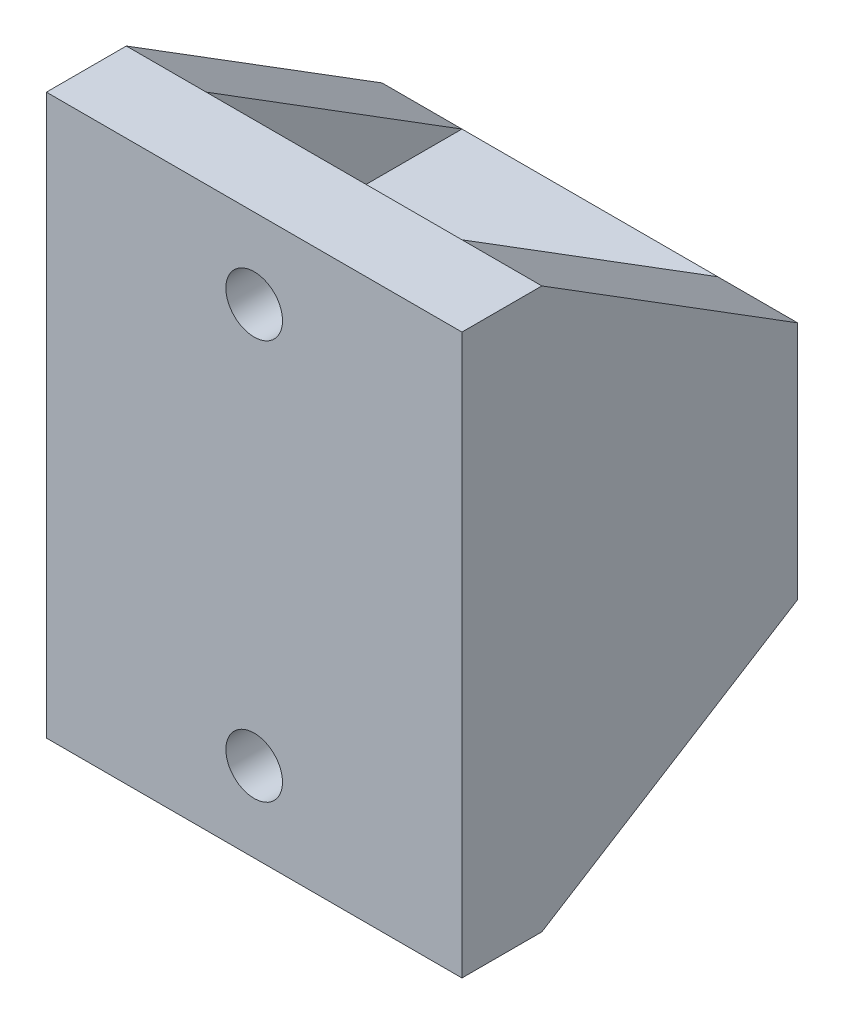
SolidWorks part; units mm, degrees
ref_plane "Face" through (0, 0, 0) normal (0, 0, 1) x (1, 0, 0)
ref_plane "Dessus" through (0, 0, 0) normal (0, 1, 0) x (1, 0, 0)
ref_plane "Droite" through (0, 0, 0) normal (1, 0, 0) x (0, 0, -1)
sketch "Esquisse1" plane through (0, 0, 0) normal (0, 0, 1) x (1, 0, 0)
  line L0 (-13.716, 4.3815) -> (-13.716, -4.3815)
  line L1 (-16.51, 9.525) -> (16.51, 9.525)
  line L2 (-16.51, 9.525) -> (-16.51, -9.525)
  line L3 (-16.51, -9.525) -> (16.51, -9.525)
  line L4 (16.51, 9.525) -> (16.51, -9.525)
  line L5 (-16.51, 9.525) -> (16.51, -9.525) construction
  line L6 (-16.51, -9.525) -> (16.51, 9.525) construction
  line L7 (-13.716, -4.3815) -> (13.716, -4.3815)
  line L8 (13.716, -4.3815) -> (13.716, 4.3815)
  line L9 (13.716, 4.3815) -> (10.16, 4.3815)
  line L10 (10.16, 4.3815) -> (10.16, -0.5715)
  line L11 (10.16, -0.5715) -> (-10.16, -0.5715)
  line L12 (-10.16, -0.5715) -> (-10.16, 4.3815)
  line L13 (-10.16, 4.3815) -> (-13.716, 4.3815)
  point P0 (0, 0)
  dimension "D1" = 33.02
  dimension "D2" = 19.05
  dimension "D3" = 20.32
  dimension "D4" = 4.953
  dimension "D5" = 3.81
  dimension "D6" = 3.556
  dimension "D7" = 3.556
  dimension "D8" = 2.794
  dimension "D9" = 5.1435
extrude "Boss.-Extru.1" add sketch "Esquisse1" along normal blind 20.32
sketch "Esquisse2" plane through (0, 9.525, 0) normal (0, 1, 0) x (1, 0, 0)
  line L0 (16.51, -20.32) -> (-16.51, -20.32) construction
  circle A0 centre (0, -10.287) radius 2.4765
  dimension "D1" = 4.953
  dimension "D2" = 10.033
extrude "Enlèv. mat.-Extru.1" cut sketch "Esquisse2" against normal through all
sketch "Esquisse3" plane through (0, 0, 20.32) normal (0, 0, 1) x (1, 0, 0)
  line L0 (16.51, -9.525) -> (16.51, 9.525) construction
  line L1 (-16.51, 22.225) -> (16.51, 22.225)
  line L2 (-16.51, 22.225) -> (-16.51, -22.225)
  line L3 (-16.51, -22.225) -> (16.51, -22.225)
  line L4 (16.51, 22.225) -> (16.51, -22.225)
  line L7 (-16.51, -9.525) -> (16.51, -9.525) construction
  line L8 (-16.51, 9.525) -> (-16.51, -9.525) construction
  dimension "D1" = 44.45
  dimension "D2" = 12.7
extrude "Boss.-Extru.2" add sketch "Esquisse3" along normal blind 6.35
sketch "Esquisse5" plane through (16.51, 0, 0) normal (1, 0, 0) x (0, 0, -1)
  line L0 (-20.32, -22.225) -> (0, -9.525)
  line L1 (0, -9.525) -> (-20.32, -9.525)
  line L2 (-20.32, -22.225) -> (-20.32, -9.525) construction
  line L3 (-20.32, -9.525) -> (0, -9.525) construction
  line L4 (-20.32, -9.525) -> (-20.32, -22.225)
  line L5 (-20.32, 22.225) -> (0, 9.525)
  line L6 (0, 9.525) -> (-20.32, 9.525)
  line L7 (-20.32, 9.525) -> (-20.32, 22.225)
extrude "Boss.-Extru.3" add sketch "Esquisse5" against normal blind 6.35
mirror "Symétrie1" about plane through (0, 0, 0) normal (1, 0, 0) of "Boss.-Extru.3"
sketch "Esquisse6" plane through (0, 0, 20.32) normal (0, 0, -1) x (-1, 0, 0)
  line L0 (55, 0) -> (-55, 0) construction
  line L1 (10.16, -22.225) -> (-10.16, -22.225) construction
  circle A0 centre (0, -15.875) radius 2.25
  circle A1 centre (0, 15.875) radius 2.25
  point P6 (0, 0)
  dimension "D1" = 4.5
  dimension "D2" = 6.35
extrude "Enlèv. mat.-Extru.2" cut sketch "Esquisse6" against normal through all
